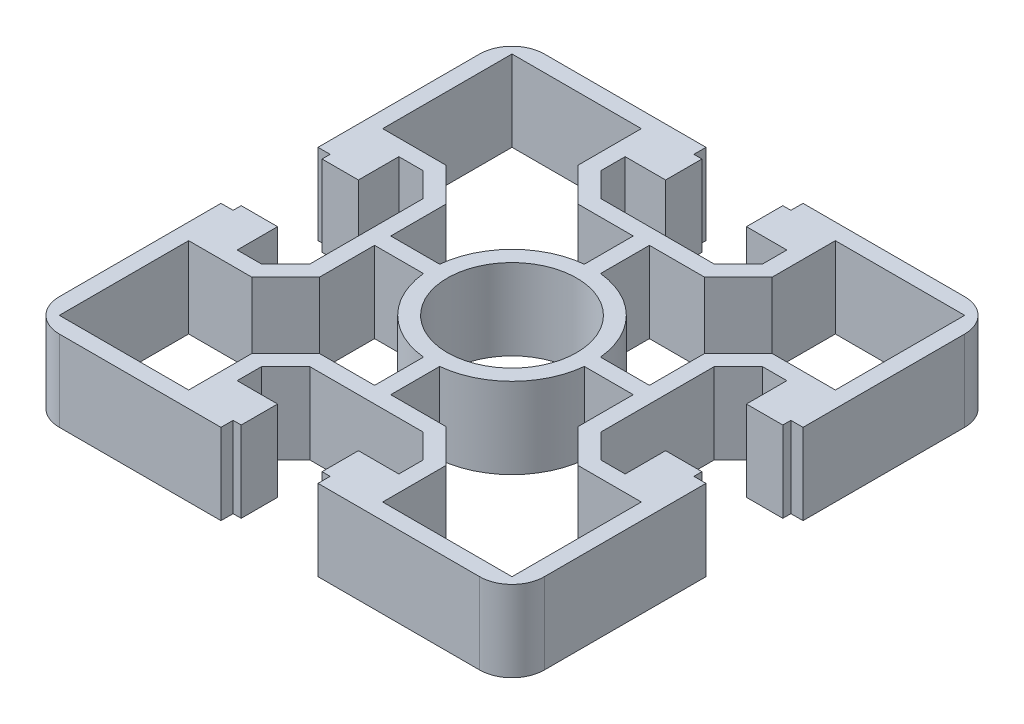
SolidWorks part; units mm, degrees
ref_plane "前视基准面" through (0, 0, 0) normal (0, 0, 1) x (1, 0, 0)
ref_plane "上视基准面" through (0, 0, 0) normal (0, 1, 0) x (1, 0, 0)
ref_plane "右视基准面" through (0, 0, 0) normal (1, 0, 0) x (0, 0, -1)
sketch "草图1" plane through (0, 0, 0) normal (0, 1, 0) x (1, 0, 0)
  line L0 (0, 32.6515) -> (0, -47.5) construction
  line L2 (-54.5455, 0) -> (57.7273, 0) construction
  line L82 (-16, 1) -> (-9.9499, 1)
  line L83 (-30, 6) -> (-28.5, 6)
  line L88 (-16, 1) -> (-16, 7.8284)
  line L89 (-16, 7.8284) -> (-20.1716, 12)
  line L90 (-20.1716, 12) -> (-28, 12)
  line L91 (-28, 12) -> (-28, 28)
  line L92 (-28, 28) -> (-12, 28)
  line L93 (-12, 28) -> (-12, 20.1716)
  line L94 (-12, 20.1716) -> (-7.8284, 16)
  line L95 (-7.8284, 16) -> (-1, 16)
  line L96 (-1, 16) -> (-1, 9.9499)
  line L97 (1, 9.9499) -> (1, 16)
  line L98 (1, 16) -> (7.8284, 16)
  line L99 (7.8284, 16) -> (12, 20.1716)
  line L100 (12, 20.1716) -> (12, 28)
  line L101 (12, 28) -> (28, 28)
  line L102 (28, 28) -> (28, 12)
  line L103 (28, 12) -> (20.1716, 12)
  line L104 (20.1716, 12) -> (16, 7.8284)
  line L105 (16, 7.8284) -> (16, 1)
  line L106 (16, 1) -> (9.9499, 1)
  line L107 (9.9499, -1) -> (16, -1)
  line L108 (16, -1) -> (16, -7.8284)
  line L109 (16, -7.8284) -> (20.1716, -12)
  line L110 (20.1716, -12) -> (28, -12)
  line L111 (28, -12) -> (28, -28)
  line L112 (28, -28) -> (12, -28)
  line L113 (12, -28) -> (12, -20.1716)
  line L114 (12, -20.1716) -> (7.8284, -16)
  line L115 (7.8284, -16) -> (1, -16)
  line L116 (1, -16) -> (1, -9.9499)
  line L117 (-1, -9.9499) -> (-1, -16)
  line L118 (-1, -16) -> (-7.8284, -16)
  line L119 (-7.8284, -16) -> (-12, -20.1716)
  line L120 (-12, -20.1716) -> (-12, -28)
  line L121 (-12, -28) -> (-28, -28)
  line L122 (-28, -28) -> (-28, -12)
  line L123 (-28, -12) -> (-20.1716, -12)
  line L124 (-20.1716, -12) -> (-16, -7.8284)
  line L125 (-16, -7.8284) -> (-16, -1)
  line L126 (-28.5, 6) -> (-28.5, 5)
  line L127 (-28.5, 5) -> (-24, 5)
  line L128 (-24, 5) -> (-24, 10)
  line L129 (-24, 10) -> (-21, 10)
  line L130 (-21, 10) -> (-18, 7)
  line L131 (-18, 7) -> (-18, -7)
  line L132 (-18, -7) -> (-21, -10)
  line L133 (-21, -10) -> (-24, -10)
  line L134 (-24, -10) -> (-24, -5)
  line L135 (-24, -5) -> (-28.5, -5)
  line L136 (-28.5, -5) -> (-28.5, -6)
  line L137 (-28.5, -6) -> (-30, -6)
  line L138 (-30, -6) -> (-30, -26)
  line L139 (-26, -30) -> (-6, -30)
  line L140 (-6, -30) -> (-6, -28.5)
  line L141 (-6, -28.5) -> (-5, -28.5)
  line L142 (-5, -28.5) -> (-5, -24)
  line L143 (-5, -24) -> (-10, -24)
  line L144 (-10, -24) -> (-10, -21)
  line L145 (-10, -21) -> (-7, -18)
  line L146 (-7, -18) -> (7, -18)
  line L147 (7, -18) -> (10, -21)
  line L148 (10, -21) -> (10, -24)
  line L149 (10, -24) -> (5, -24)
  line L150 (5, -24) -> (5, -28.5)
  line L151 (5, -28.5) -> (6, -28.5)
  line L152 (6, -28.5) -> (6, -30)
  line L153 (6, -30) -> (26, -30)
  line L154 (30, -26) -> (30, -6)
  line L155 (30, -6) -> (28.5, -6)
  line L156 (28.5, -6) -> (28.5, -5)
  line L157 (28.5, -5) -> (24, -5)
  line L158 (24, -5) -> (24, -10)
  line L159 (24, -10) -> (21, -10)
  line L160 (21, -10) -> (18, -7)
  line L161 (18, -7) -> (18, 7)
  line L162 (18, 7) -> (21, 10)
  line L163 (21, 10) -> (24, 10)
  line L164 (24, 10) -> (24, 5)
  line L165 (24, 5) -> (28.5, 5)
  line L166 (28.5, 5) -> (28.5, 6)
  line L167 (28.5, 6) -> (30, 6)
  line L168 (30, 6) -> (30, 26)
  line L169 (26, 30) -> (6, 30)
  line L170 (6, 30) -> (6, 28.5)
  line L171 (6, 28.5) -> (5, 28.5)
  line L172 (5, 28.5) -> (5, 24)
  line L173 (5, 24) -> (10, 24)
  line L174 (10, 24) -> (10, 21)
  line L175 (10, 21) -> (7, 18)
  line L176 (7, 18) -> (-7, 18)
  line L177 (-7, 18) -> (-10, 21)
  line L178 (-10, 21) -> (-10, 24)
  line L179 (-10, 24) -> (-5, 24)
  line L180 (-5, 24) -> (-5, 28.5)
  line L181 (-5, 28.5) -> (-6, 28.5)
  line L182 (-6, 28.5) -> (-6, 30)
  line L183 (-6, 30) -> (-26, 30)
  line L184 (-30, 26) -> (-30, 6)
  line L185 (-16, -1) -> (-9.9499, -1)
  arc A41 (-9.9499, -1) -> (-1, -9.9499) centre (0, 0) ccw
  circle A42 centre (0, 0) radius 8
  arc A43 (-26, -30) -> (-30, -26) centre (-26, -26) cw
  arc A44 (26, 30) -> (30, 26) centre (26, 26) cw
  arc A45 (-26, 30) -> (-30, 26) centre (-26, 26) ccw
  arc A46 (26, -30) -> (30, -26) centre (26, -26) ccw
  arc A47 (9.9499, 1) -> (1, 9.9499) centre (0, 0) ccw
  arc A48 (-1, 9.9499) -> (-9.9499, 1) centre (0, 0) ccw
  arc A49 (1, -9.9499) -> (9.9499, -1) centre (0, 0) ccw
extrude "凸台-拉伸1" add sketch "草图1" along normal blind 10
